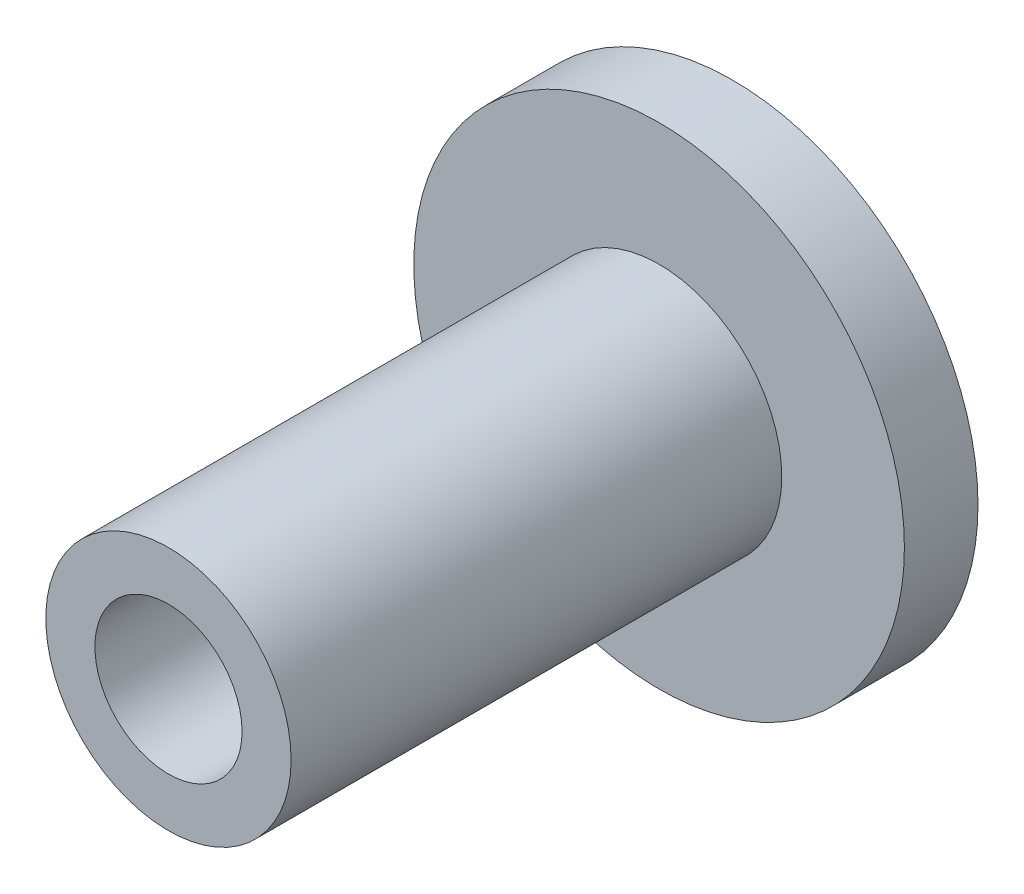
SolidWorks part; units mm, degrees
ref_plane "Front Plane" through (0, 0, 0) normal (0, 0, 1) x (1, 0, 0)
ref_plane "Top Plane" through (0, 0, 0) normal (0, 1, 0) x (1, 0, 0)
ref_plane "Right Plane" through (0, 0, 0) normal (1, 0, 0) x (0, 0, -1)
sketch "Sketch1" plane through (0, 0, 0) normal (0, 0, 1) x (1, 0, 0)
  circle A0 centre (0, 0) radius 10
  dimension "D1" = 20
extrude "Boss-Extrude1" add sketch "Sketch1" along normal blind 3
sketch "Sketch2" plane through (0, 0, 3) normal (0, 0, 1) x (1, 0, 0)
  circle A0 centre (0, 0) radius 5
  dimension "D1" = 10
extrude "Boss-Extrude2" add sketch "Sketch2" along normal blind 20
sketch "Sketch3" plane through (0, 0, 23) normal (0, 0, 1) x (1, 0, 0)
  circle A0 centre (0, 0) radius 3
  dimension "D1" = 6
extrude "Cut-Extrude1" cut sketch "Sketch3" against normal through all
